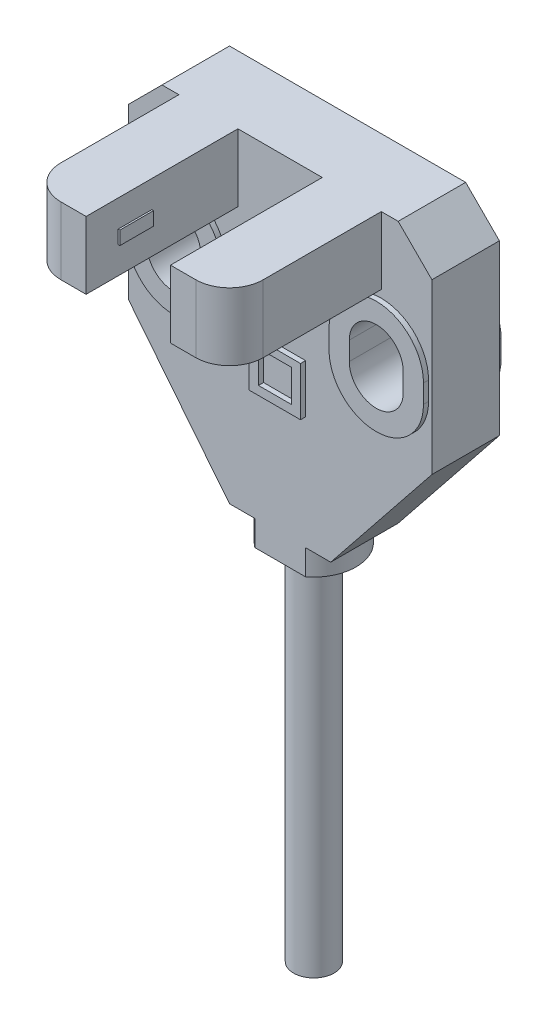
SolidWorks part; units mm, degrees
material "橡膠"
ref_plane "前基準面" through (0, 0, 0) normal (0, 0, 1) x (1, 0, 0)
ref_plane "上基準面" through (0, 0, 0) normal (0, 1, 0) x (1, 0, 0)
ref_plane "右基準面" through (0, 0, 0) normal (1, 0, 0) x (0, 0, -1)
sketch "草圖1" plane through (0, 0, 0) normal (0, 0, 1) x (1, 0, 0)
  line L1 (-9, 0) -> (9, 0)
  line L2 (-9, 0) -> (-9, -12)
  line L3 (0, 0) -> (0, -12) construction
  line L4 (9, 0) -> (9, -12)
  line L5 (-3, -19.5) -> (3, -19.5)
  line L6 (-9, -12) -> (-3, -19.5)
  line L9 (3, -19.5) -> (9, -12)
  dimension "D1" = 19.5
  dimension "D2" = 18
  dimension "D3" = 6
  dimension "D4" = 12
extrude "伸長1" add sketch "草圖1" along normal blind 4
sketch "草圖2" plane through (0, 0, 0) normal (0, 1, 0) x (1, 0, 0)
  line L1 (-6, -4) -> (-2.5, -4)
  line L2 (-6, -4) -> (-6, -11)
  line L3 (-4, -13) -> (-2.5, -13)
  line L4 (-2.5, -4) -> (-2.5, -13)
  line L5 (0, -6.0558) -> (0, -1.6852) construction
  line L6 (2.5, -4) -> (6, -4)
  line L7 (2.5, -4) -> (2.5, -13)
  line L8 (2.5, -13) -> (4, -13)
  line L9 (6, -4) -> (6, -11)
  line L10 (9, -4) -> (-9, -4) construction
  arc A0 (6, -11) -> (4, -13) centre (4, -11) cw
  arc A1 (-6, -11) -> (-4, -13) centre (-4, -11) ccw
  dimension "D4" = 2
  dimension "D1" = 5
  dimension "D2" = 12
  dimension "D3" = 9
extrude "伸長2" add sketch "草圖2" against normal blind 4
sketch "草圖3" plane through (0, -19.5, 0) normal (0, -1, 0) x (1, 0, 0)
  line L0 (-3, 0) -> (3, 4) construction
  line L5 (-3, 0) -> (3, 0)
  line L6 (3, 0) -> (3, 4)
  line L7 (3, 4) -> (-3, 4)
  line L8 (-3, 4) -> (-3, 0)
  line L9 (-1.5, 0) -> (1.5, 0)
  line L11 (1.5, 4) -> (-1.5, 4)
  arc A0 (-1.5, 4) -> (-1.5, 0) centre (0, 2) ccw
  arc A1 (1.5, 0) -> (1.5, 4) centre (0, 2) ccw
  dimension "D1" = 5
  dimension "D2" = 0
extrude "伸長3" add sketch "草圖3" along normal blind 1.5
sketch "草圖4" plane through (0, -21, 0) normal (0, -1, 0) x (1, 0, 0)
  circle A0 centre (0, 2) radius 1.2
  dimension "D1" = 2.4
extrude "伸長4" add sketch "草圖4" along normal blind 21.5
chamfer "導角1" distance 2 angle 45 2 edges at (9, 0, 2) (-9, 0, 2)
sketch "草圖5" plane through (-2.5, 0, 0) normal (1, 0, 0) x (0, 0, -1)
  line L0 (-13, -2) -> (-10.1, -2) construction
  line L1 (-11.1, -1.6) -> (-9.1, -1.6)
  line L2 (-11.1, -1.6) -> (-11.1, -2.4)
  line L3 (-11.1, -2.4) -> (-9.1, -2.4)
  line L4 (-9.1, -1.6) -> (-9.1, -2.4)
  line L5 (-13, -4) -> (-13, 0) construction
  line L6 (-10.1, -2) -> (-10.1, -2.4576) construction
  dimension "D1" = 2.9
  dimension "D2" = 0.8
  dimension "D3" = 2
sketch "草圖6" plane through (2.5, 0, 0) normal (-1, 0, 0) x (0, 0, 1)
  line L4 (11.1, -1.6) -> (9.1, -1.6)
  line L5 (9.1, -1.6) -> (9.1, -2.4)
  line L6 (9.1, -2.4) -> (11.1, -2.4)
  line L7 (11.1, -2.4) -> (11.1, -1.6)
  line L8 (11.1, -1.6) -> (9.1, -1.6)
  line L9 (9.1, -1.6) -> (9.1, -2.4)
  line L10 (9.1, -2.4) -> (11.1, -2.4)
  line L11 (11.1, -2.4) -> (11.1, -1.6)
  dimension "D1" = 0
extrude "伸長7" add sketch "草圖5" along normal blind 0.1
extrude "除料-伸長2" cut sketch "草圖6" against normal blind 0.1
sketch "草圖7" plane through (0, 0, 4) normal (0, 0, 1) x (1, 0, 0)
  line L0 (-6, -7.25) -> (-6, -8.35) construction
  line L1 (6, -7.25) -> (6, -8.35) construction
  line L2 (0, 0) -> (0, -6.0878) construction
  line L3 (-6, 0) -> (-7, 0) construction
  line L4 (-7.6, -7.25) -> (-7.6, -8.35)
  line L5 (-4.4, -7.25) -> (-4.4, -8.35)
  line L6 (4.4, -7.25) -> (4.4, -8.35)
  line L7 (7.6, -7.25) -> (7.6, -8.35)
  arc A0 (-7.6, -7.25) -> (-4.4, -7.25) centre (-6, -7.25) cw
  arc A1 (-7.6, -8.35) -> (-4.4, -8.35) centre (-6, -8.35) ccw
  arc A2 (4.4, -7.25) -> (7.6, -7.25) centre (6, -7.25) cw
  arc A3 (4.4, -8.35) -> (7.6, -8.35) centre (6, -8.35) ccw
  point P7 (-6, -7.8)
  dimension "D5" = 4.3
  dimension "D1" = 12
  dimension "D2" = 7.8
  dimension "D3" = 1.6
  dimension "D4" = 1.6
  dimension "D6" = 1.6
  dimension "D7" = 1.6
extrude "除料-伸長3" cut sketch "草圖7" against normal up to next
sketch "草圖8" plane through (0, 0, 4) normal (0, 0, 1) x (1, 0, 0)
  line L4 (3.2, -7.25) -> (3.2, -8.35)
  line L5 (8.8, -8.35) -> (8.8, -7.25)
  line L6 (3.2, -7.25) -> (3.2, -8.35)
  line L7 (8.8, -8.35) -> (8.8, -7.25)
  line L8 (4.4, -7.25) -> (4.4, -8.35) construction
  line L9 (7.6, -8.35) -> (7.6, -7.25) construction
  line L10 (4.4, -7.25) -> (4.4, -8.35)
  line L11 (7.6, -8.35) -> (7.6, -7.25)
  line L12 (-7.6, -7.25) -> (-7.6, -8.35) construction
  line L13 (-4.4, -8.35) -> (-4.4, -7.25) construction
  line L14 (-8.8, -7.25) -> (-8.8, -8.35)
  line L15 (-3.2, -8.35) -> (-3.2, -7.25)
  line L16 (-8.8, -7.25) -> (-8.8, -8.35)
  line L17 (-3.2, -8.35) -> (-3.2, -7.25)
  line L18 (-7.6, -7.25) -> (-7.6, -8.35)
  line L19 (-4.4, -8.35) -> (-4.4, -7.25)
  arc A4 (3.2, -8.35) -> (8.8, -8.35) centre (6, -8.35) ccw
  arc A5 (8.8, -7.25) -> (3.2, -7.25) centre (6, -7.25) ccw
  arc A6 (3.2, -8.35) -> (8.8, -8.35) centre (6, -8.35) ccw
  arc A7 (8.8, -7.25) -> (3.2, -7.25) centre (6, -7.25) ccw
  arc A8 (4.4, -8.35) -> (7.6, -8.35) centre (6, -8.35) ccw construction
  arc A9 (7.6, -7.25) -> (4.4, -7.25) centre (6, -7.25) ccw construction
  arc A10 (4.4, -8.35) -> (7.6, -8.35) centre (6, -8.35) ccw
  arc A11 (7.6, -7.25) -> (4.4, -7.25) centre (6, -7.25) ccw
  arc A12 (-7.6, -8.35) -> (-4.4, -8.35) centre (-6, -8.35) ccw construction
  arc A13 (-4.4, -7.25) -> (-7.6, -7.25) centre (-6, -7.25) ccw construction
  arc A14 (-8.8, -8.35) -> (-3.2, -8.35) centre (-6, -8.35) ccw
  arc A15 (-3.2, -7.25) -> (-8.8, -7.25) centre (-6, -7.25) ccw
  arc A16 (-8.8, -8.35) -> (-3.2, -8.35) centre (-6, -8.35) ccw
  arc A17 (-3.2, -7.25) -> (-8.8, -7.25) centre (-6, -7.25) ccw
  arc A18 (-7.6, -8.35) -> (-4.4, -8.35) centre (-6, -8.35) ccw
  arc A19 (-4.4, -7.25) -> (-7.6, -7.25) centre (-6, -7.25) ccw
  dimension "D1" = 1.2
  dimension "D3" = 1.2
extrude "伸長8" add sketch "草圖8" along normal blind 0.3
sketch "草圖9" plane through (0, 0, 0) normal (0, 0, -1) x (-1, 0, 0)
  line L2 (-4.4, -8.35) -> (-4.4, -7.25)
  line L3 (-7.6, -7.25) -> (-7.6, -8.35)
  line L4 (-4.4, -8.35) -> (-4.4, -7.25)
  line L5 (-7.6, -7.25) -> (-7.6, -8.35)
  line L6 (-3.2, -8.35) -> (-3.2, -7.25)
  line L7 (-8.8, -7.25) -> (-8.8, -8.35)
  line L8 (-3.2, -8.35) -> (-3.2, -7.25)
  line L9 (-8.8, -7.25) -> (-8.8, -8.35)
  line L10 (7.6, -8.35) -> (7.6, -7.25)
  line L11 (4.4, -7.25) -> (4.4, -8.35)
  line L12 (7.6, -8.35) -> (7.6, -7.25)
  line L13 (4.4, -7.25) -> (4.4, -8.35)
  line L14 (8.8, -8.35) -> (8.8, -7.25)
  line L15 (3.2, -7.25) -> (3.2, -8.35)
  line L16 (8.8, -8.35) -> (8.8, -7.25)
  line L17 (3.2, -7.25) -> (3.2, -8.35)
  arc A2 (-7.6, -8.35) -> (-4.4, -8.35) centre (-6, -8.35) ccw
  arc A3 (-4.4, -7.25) -> (-7.6, -7.25) centre (-6, -7.25) ccw
  arc A4 (-7.6, -8.35) -> (-4.4, -8.35) centre (-6, -8.35) ccw
  arc A5 (-4.4, -7.25) -> (-7.6, -7.25) centre (-6, -7.25) ccw
  arc A6 (-8.8, -8.35) -> (-3.2, -8.35) centre (-6, -8.35) ccw
  arc A7 (-3.2, -7.25) -> (-8.8, -7.25) centre (-6, -7.25) ccw
  arc A8 (-8.8, -8.35) -> (-3.2, -8.35) centre (-6, -8.35) ccw
  arc A9 (-3.2, -7.25) -> (-8.8, -7.25) centre (-6, -7.25) ccw
  arc A10 (4.4, -8.35) -> (7.6, -8.35) centre (6, -8.35) ccw
  arc A11 (7.6, -7.25) -> (4.4, -7.25) centre (6, -7.25) ccw
  arc A12 (4.4, -8.35) -> (7.6, -8.35) centre (6, -8.35) ccw
  arc A13 (7.6, -7.25) -> (4.4, -7.25) centre (6, -7.25) ccw
  arc A14 (3.2, -8.35) -> (8.8, -8.35) centre (6, -8.35) ccw
  arc A15 (8.8, -7.25) -> (3.2, -7.25) centre (6, -7.25) ccw
  arc A16 (3.2, -8.35) -> (8.8, -8.35) centre (6, -8.35) ccw
  arc A17 (8.8, -7.25) -> (3.2, -7.25) centre (6, -7.25) ccw
  dimension "D1" = 0
  dimension "D2" = 0
  dimension "D3" = 0
  dimension "D4" = 0
extrude "伸長9" add sketch "草圖9" along normal blind 0.3
sketch "草圖10" plane through (0, 0, 4) normal (0, 0, 1) x (1, 0, 0)
  line L0 (0, -2.027) -> (0, -15.7811) construction
  line L1 (-0.9824, -10.359) -> (0.9824, -10.359)
  line L2 (-0.9824, -10.359) -> (-0.9824, -12.2681)
  line L3 (-0.9824, -12.2681) -> (0.9824, -12.2681)
  line L4 (0.9824, -10.359) -> (0.9824, -12.2681)
  line L6 (-1.5339, -9.8946) -> (1.5104, -9.8946)
  line L7 (-1.5339, -9.8946) -> (-1.5339, -12.7841)
  line L8 (-1.5339, -12.7841) -> (1.5104, -12.7841)
  line L9 (1.5104, -9.8946) -> (1.5104, -12.7841)
extrude "伸長10" add sketch "草圖10" along normal blind 0.3
